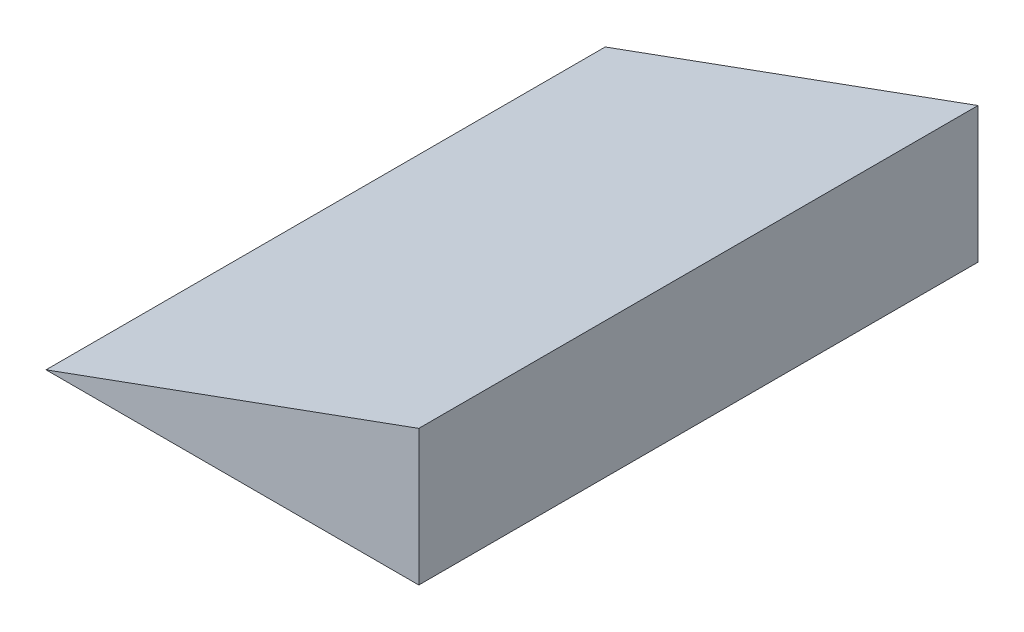
SolidWorks part; units mm, degrees
ref_plane "Front Plane" through (0, 0, 0) normal (0, 0, 1) x (1, 0, 0)
ref_plane "Top Plane" through (0, 0, 0) normal (0, 1, 0) x (1, 0, 0)
ref_plane "Right Plane" through (0, 0, 0) normal (1, 0, 0) x (0, 0, -1)
sketch "Sketch1" plane through (0, 0, 0) normal (0, 0, 1) x (1, 0, 0)
  line L0 (-2000, 0) -> (2000, 0)
  line L1 (-2000, 0) -> (2000, 1455.8809)
  line L2 (2000, 1455.8809) -> (2000, 0)
  point P4 (0, 0)
  dimension "D1" = 20
  dimension "D2" = 4000
extrude "Boss-Extrude1" add sketch "Sketch1" along normal blind 6000
